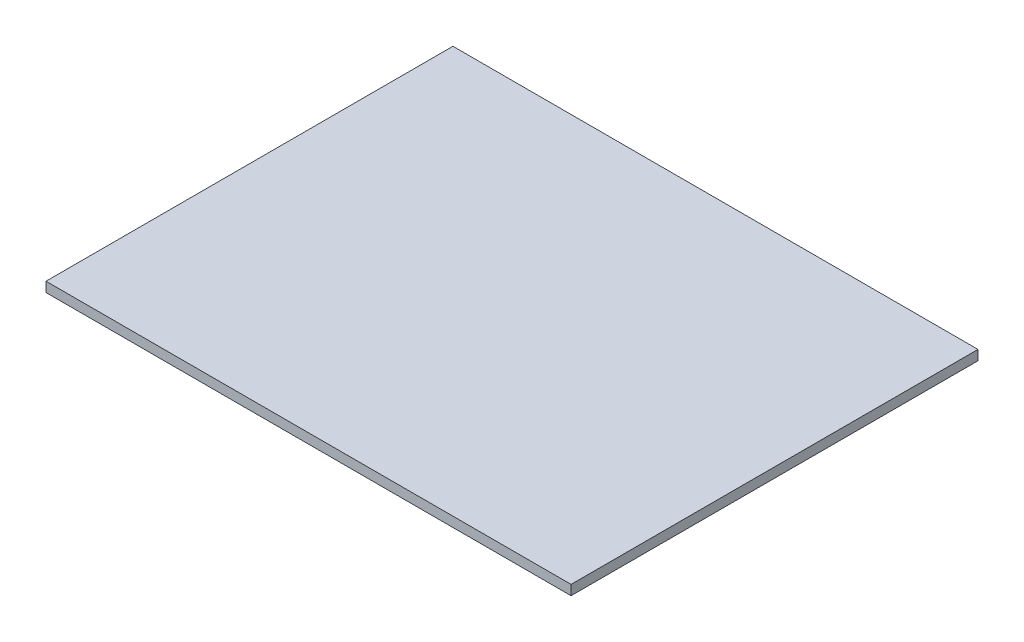
SolidWorks part; units mm, degrees
material "松木"
ref_plane "前视基准面" through (0, 0, 0) normal (0, 0, 1) x (1, 0, 0)
ref_plane "上视基准面" through (0, 0, 0) normal (0, 1, 0) x (1, 0, 0)
ref_plane "右视基准面" through (0, 0, 0) normal (1, 0, 0) x (0, 0, -1)
other "Configuration Table"
sketch "草图1" plane through (0, 0, 0) normal (0, 1, 0) x (1, 0, 0)
  line L1 (-400, 620) -> (400, 620)
  line L2 (-400, 620) -> (-400, 0)
  line L3 (-400, 0) -> (400, 0)
  line L4 (400, 620) -> (400, 0)
  point P4 (0, 0)
  dimension "D1" = 620
  dimension "D2" = 800
extrude "凸台-拉伸1" add sketch "草图1" along normal blind 15
